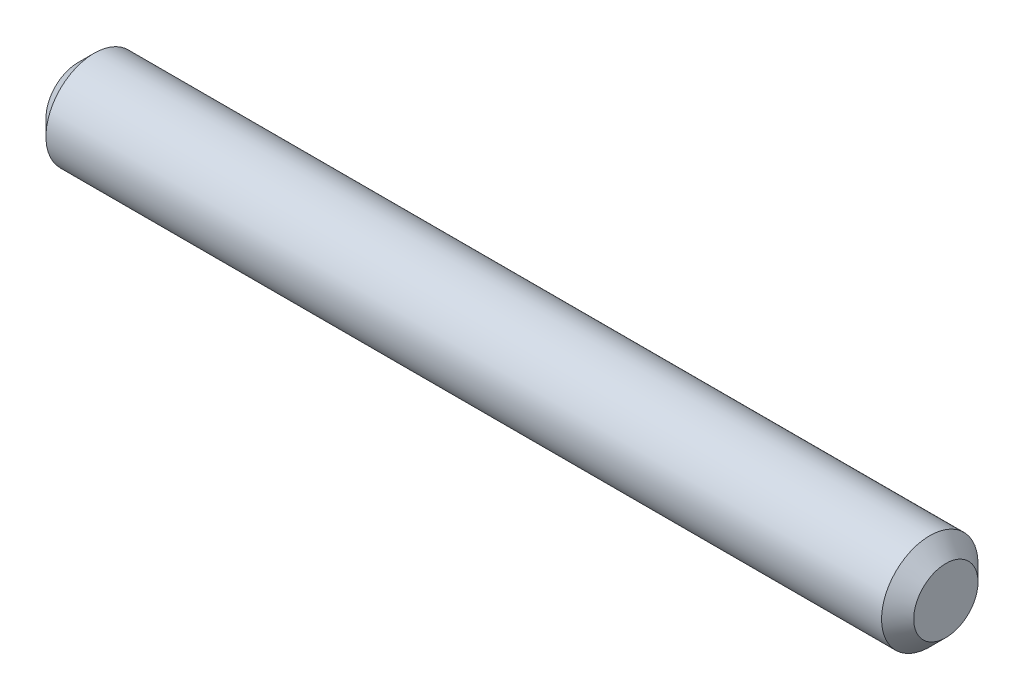
SolidWorks part; units mm, degrees
ref_plane "Piano frontale" through (0, 0, 0) normal (0, 0, 1) x (1, 0, 0)
ref_plane "Piano superiore" through (0, 0, 0) normal (0, 1, 0) x (1, 0, 0)
ref_plane "Piano destro" through (0, 0, 0) normal (1, 0, 0) x (0, 0, -1)
sketch "Schizzo1" plane through (0, 0, 0) normal (1, 0, 0) x (0, 0, -1)
  circle A0 centre (0, 0) radius 3
  dimension "D1" = 6
extrude "Estrusione-Estrusione1" add sketch "Schizzo1" along normal blind 54
chamfer "Smusso1" distance 1 angle 45 2 edges at (0, 0, -3) (54, 0, -3)
